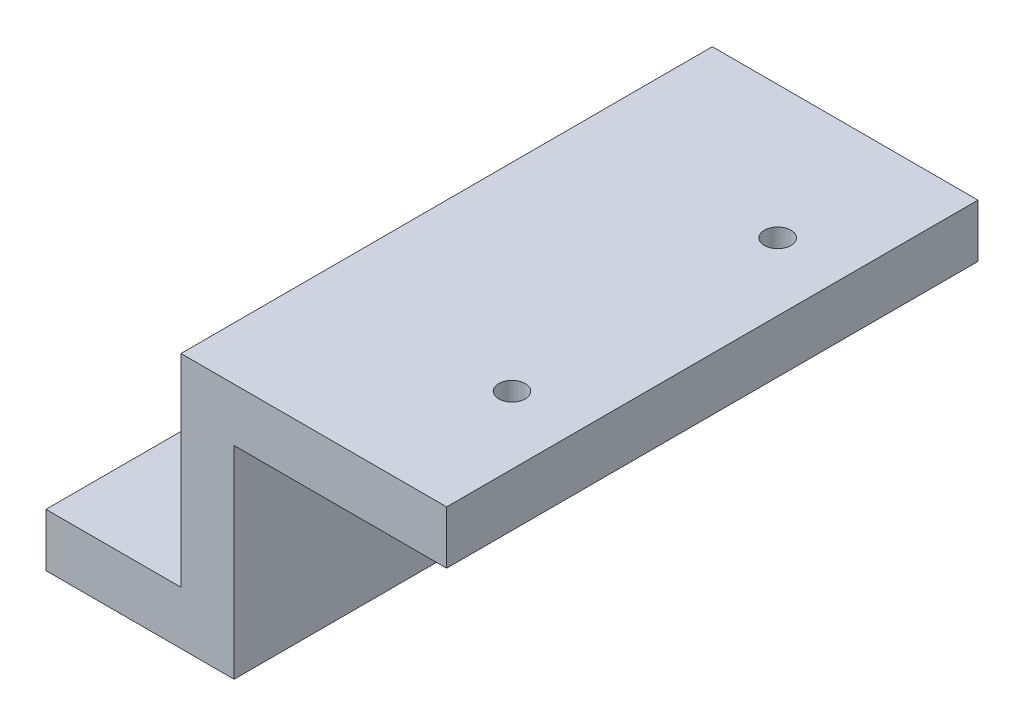
SolidWorks part; units mm, degrees
material "ABS"
ref_plane "Front Plane" through (0, 0, 0) normal (0, 0, 1) x (1, 0, 0)
ref_plane "Top Plane" through (0, 0, 0) normal (0, 1, 0) x (1, 0, 0)
ref_plane "Right Plane" through (0, 0, 0) normal (1, 0, 0) x (0, 0, -1)
sketch "Sketch1" plane through (0, 0, 0) normal (0, 0, 1) x (1, 0, 0)
  line L1 (-25, -5) -> (25, -5)
  line L2 (-25, -5) -> (-25, 5)
  line L3 (-25, 5) -> (25, 5)
  line L4 (25, -5) -> (25, 5)
  line L5 (-25, -5) -> (25, 5) construction
  line L6 (-25, 5) -> (25, -5) construction
  point P0 (0, 0)
  dimension "D1" = 10
  dimension "D2" = 50
extrude "Boss-Extrude1" add sketch "Sketch1" along normal blind 100
sketch "Sketch2" plane through (0, -5, 0) normal (0, -1, 0) x (1, 0, 0)
  line L0 (-25, 0) -> (25, 0) construction
  line L1 (-25, 100) -> (-15, 100)
  line L2 (-25, 100) -> (-25, 0)
  line L3 (-25, 0) -> (-15, 0)
  line L4 (-15, 100) -> (-15, 0)
  dimension "D1" = 10
extrude "Boss-Extrude2" add sketch "Sketch2" along normal blind 38.1
sketch "Sketch3" plane through (-25, 0, 0) normal (-1, 0, 0) x (0, 0, 1)
  line L0 (100, 5) -> (100, -43.1) construction
  line L1 (0, -43.1) -> (100, -43.1)
  line L2 (0, -43.1) -> (0, -33.1)
  line L3 (0, -33.1) -> (100, -33.1)
  line L4 (100, -43.1) -> (100, -33.1)
  dimension "D1" = 10
extrude "Boss-Extrude3" add sketch "Sketch3" along normal blind 25.4
sketch "Sketch4" plane through (0, 5, 0) normal (0, 1, 0) x (1, 0, 0)
  line L0 (25, -100) -> (-25, -100) construction
  line L1 (25, 0) -> (-0.4, 0)
  line L2 (25, 0) -> (25, -100)
  line L3 (25, -100) -> (-0.4, -100)
  line L4 (-0.4, 0) -> (-0.4, -100)
  line L5 (-0.4, -100) -> (25, 0) construction
  line L6 (12.3, -50) -> (12.3, 0) construction
  line L7 (12.3, -50) -> (12.3, -100) construction
  point P9 (12.3, -25)
  point P11 (12.3, -75)
  point P13 (12.3, -25)
  point P15 (12.3, -75)
  dimension "D1" = 25.4
sketch "Sketch7" plane through (-15, 0, 0) normal (1, 0, 0) x (0, 0, -1)
  line L0 (-100, -43.1) -> (-100, -5) construction
  line L1 (0, -5) -> (-100, -5)
  line L2 (0, -5) -> (0, -43.1)
  line L3 (0, -43.1) -> (-100, -43.1)
  line L4 (-100, -5) -> (-100, -43.1)
  line L8 (-50, -5) -> (-50, -43.1) construction
  line L11 (0, -43.1) -> (-100, -43.1) construction
  point P28 (-73, -26.1)
  point P31 (-27, -26.1)
  point P35 (-73, -8.1)
  point P37 (-27, -8.1)
  point P40 (0, 0)
  point P41 (-67.8594, -5.6796)
  point P42 (0, 0)
  point P43 (0, 0)
  dimension "D3" = 35
  dimension "D2" = 46
  dimension "D1" = 18
hole_wizard "M5x0.8 Tapped Hole1" positions "Sketch4" profile "Sketch8" tap size "M5x0.8" standard "ANSI Metric" end condition through all
sketch "Sketch8" plane through (12.3, 5, 75) normal (1, 0, 0) x (0, 0, 1)
  line L0 (0, 0) -> (0, 48.1)
  line L1 (0, 48.1) -> (2.5, 48.1)
  line L2 (2.5, 48.1) -> (2.5, 0)
  line L5 (2.5, 0) -> (0, 0)
  line L11 (0, -6.35) -> (0, 107.95) construction
  dimension "Thread Major Dia." = 5
  dimension "Thru Tap Drill Depth" = 48.1
hole_wizard "M5x0.8 Tapped Hole2" positions "Sketch7" profile "Sketch9" tap size "M5x0.8" standard "ANSI Metric" end condition through all
sketch "Sketch9" plane through (-15, -8.1, 27) normal (0, 1, 0) x (0, 0, -1)
  line L0 (0, 0) -> (0, 35.4)
  line L1 (0, 35.4) -> (2.5, 35.4)
  line L2 (2.5, 35.4) -> (2.5, 0)
  line L5 (2.5, 0) -> (0, 0)
  line L11 (0, -6.35) -> (0, 107.95) construction
  dimension "Thread Major Dia." = 5
  dimension "Thru Tap Drill Depth" = 35.4
